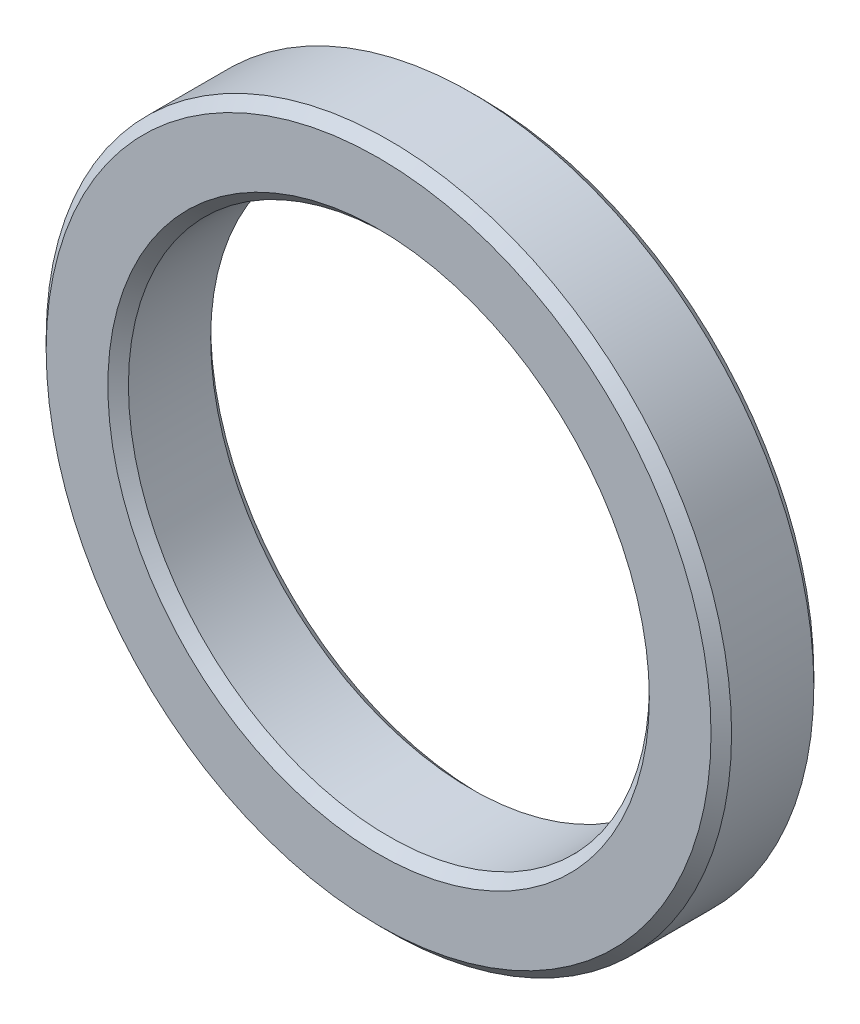
SolidWorks part; units mm, degrees
ref_plane "前视基准面" through (0, 0, 0) normal (0, 0, 1) x (1, 0, 0)
ref_plane "上视基准面" through (0, 0, 0) normal (0, 1, 0) x (1, 0, 0)
ref_plane "右视基准面" through (0, 0, 0) normal (1, 0, 0) x (0, 0, -1)
other "Configuration Table"
sketch "草图1" plane through (0, 0, 0) normal (0, 0, 1) x (1, 0, 0)
  circle A0 centre (0, 0) radius 7.6
  circle A1 centre (0, 0) radius 10
  dimension "D1" = 15.2
  dimension "D2" = 20
extrude "凸台-拉伸1" add sketch "草图1" along normal blind 3
chamfer "倒角1" distance 0.3 angle 45 4 edges at (10, 0, 0) (10, 0, 3) (7.6, 0, 0) (7.6, 0, 3)
